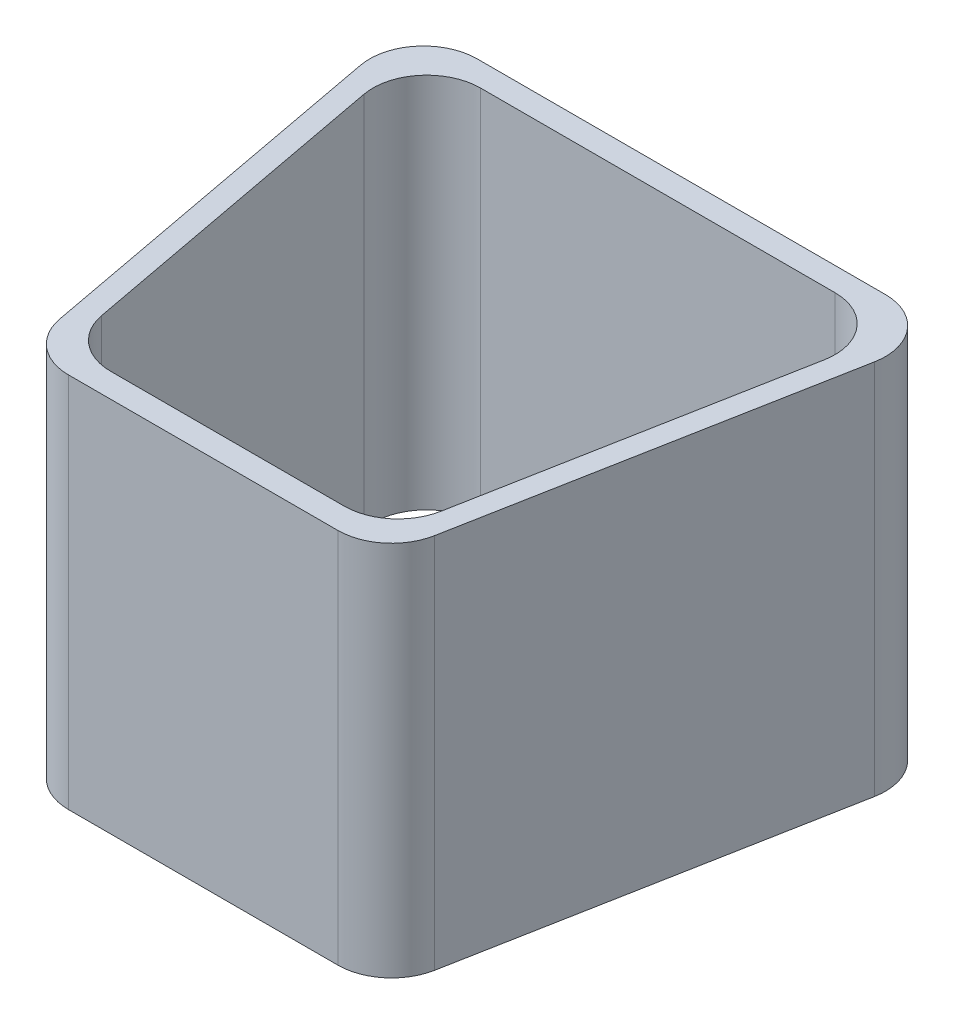
SolidWorks part; units mm, degrees
ref_plane "Front Plane" through (0, 0, 0) normal (0, 0, 1) x (1, 0, 0)
ref_plane "Top Plane" through (0, 0, 0) normal (0, 1, 0) x (1, 0, 0)
ref_plane "Right Plane" through (0, 0, 0) normal (1, 0, 0) x (0, 0, -1)
sketch "Sketch1" plane through (0, 0, 0) normal (0, 1, 0) x (1, 0, 0)
  line L0 (-9.6395, 11.2748) -> (9.6395, 11.2748)
  line L1 (-6.3587, -11.303) -> (6.3587, -11.303)
  line L2 (8.8551, -9.2311) -> (12.136, 8.2667)
  line L3 (0, 11.2748) -> (0, -11.303) construction
  line L4 (-8.8551, -9.2311) -> (-12.136, 8.2667)
  arc A0 (6.3587, -11.303) -> (8.8551, -9.2311) centre (6.3587, -8.763) ccw
  arc A1 (12.136, 8.2667) -> (9.6395, 11.2748) centre (9.6395, 8.7348) ccw
  arc A2 (-6.3587, -11.303) -> (-8.8551, -9.2311) centre (-6.3587, -8.763) cw
  arc A3 (-12.136, 8.2667) -> (-9.6395, 11.2748) centre (-9.6395, 8.7348) cw
  point P7 (8.4667, -11.303)
  point P10 (12.7, 11.2748)
  dimension "D5" = 2.54
  dimension "D1" = 22.5778
  dimension "D2" = 12.7
  dimension "D3" = 8.4667
  dimension "D4" = 11.303
extrude "Boss-Extrude1" add sketch "Sketch1" along normal mid plane 17.78
sketch "Sketch2" plane through (0, 8.89, 0) normal (0, 1, 0) x (1, 0, 0)
  line L0 (0, -1020.5715) -> (0, -10.16) construction
  line L2 (-8.3695, 10.16) -> (8.3695, 10.16)
  line L3 (10.866, 7.1519) -> (8.0085, -8.0881)
  line L4 (5.512, -10.16) -> (-5.512, -10.16)
  line L6 (-10.866, 7.1519) -> (-8.0085, -8.0881)
  line L7 (0, 10.16) -> (0, 1010.4115) construction
  arc A0 (10.866, 7.1519) -> (8.3695, 10.16) centre (8.3695, 7.62) ccw
  arc A1 (5.512, -10.16) -> (8.0085, -8.0881) centre (5.512, -7.62) ccw
  arc A2 (-10.866, 7.1519) -> (-8.3695, 10.16) centre (-8.3695, 7.62) cw
  arc A3 (-5.512, -10.16) -> (-8.0085, -8.0881) centre (-5.512, -7.62) cw
  point P11 (11.43, 10.16)
  point P14 (7.62, -10.16)
  dimension "D6" = 2.54
  dimension "D7" = 2.54
  dimension "D2" = 0
  dimension "D5" = 10.16
extrude "Cut-Extrude3" cut sketch "Sketch2" against normal through all
